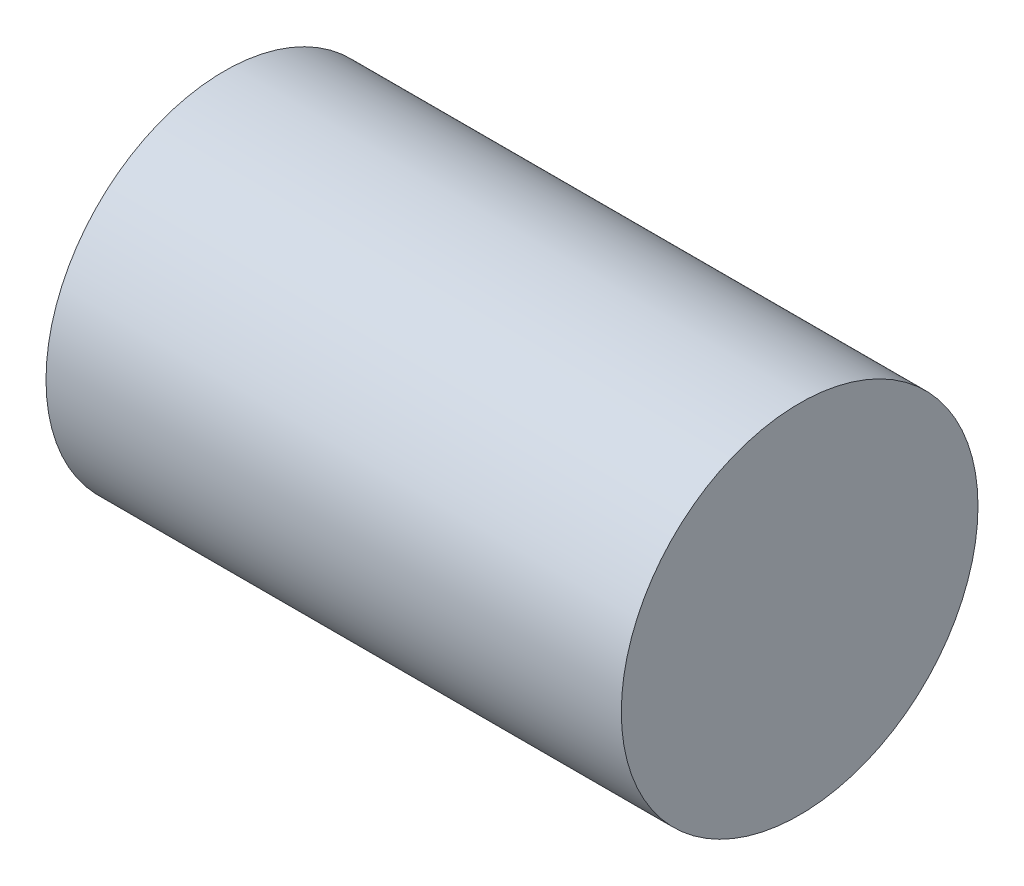
SolidWorks part; units mm, degrees
ref_plane "Front Plane" through (0, 0, 0) normal (0, 0, 1) x (1, 0, 0)
ref_plane "Top Plane" through (0, 0, 0) normal (0, 1, 0) x (1, 0, 0)
ref_plane "Right Plane" through (0, 0, 0) normal (1, 0, 0) x (0, 0, -1)
sketch "Sketch1" plane through (0, 0, 0) normal (0, 0, 1) x (1, 0, 0)
  line L0 (0, 0) -> (55, 0)
  line L1 (0, 0) -> (55, 0) construction
  line L2 (0, 0) -> (0, 5)
  line L3 (5, 15.5) -> (55, 15.5)
  line L4 (55, 0) -> (55, 15.5)
  line L5 (0, 5) -> (5, 5)
  line L6 (5, 5) -> (5, 15.5)
  dimension "D1" = 15.5
  dimension "D2" = 5
  dimension "D3" = 5
  dimension "D4" = 50
revolve "Revolve1" add sketch "Sketch1" angle 360 about L1
